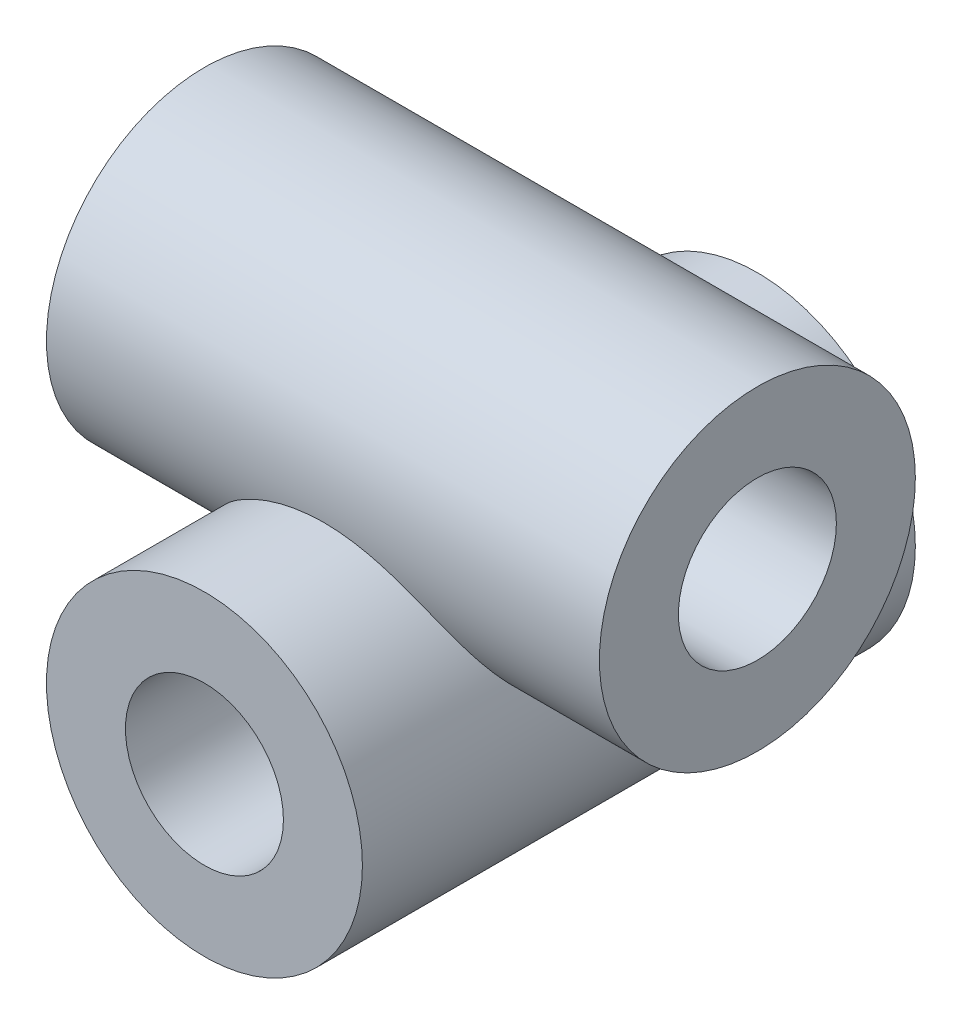
SolidWorks part; units mm, degrees
ref_plane "Front Plane" through (0, 0, 0) normal (0, 0, 1) x (1, 0, 0)
ref_plane "Top Plane" through (0, 0, 0) normal (0, 1, 0) x (1, 0, 0)
ref_plane "Right Plane" through (0, 0, 0) normal (1, 0, 0) x (0, 0, -1)
sketch "Sketch2" plane through (0, 0, 0) normal (0, 0, 1) x (1, 0, 0)
  circle A0 centre (0, 0) radius 16
  circle A1 centre (0, 0) radius 8
  dimension "D1" = 32
  dimension "D2" = 16
extrude "Boss-Extrude1" add sketch "Sketch2" along normal blind 56
sketch "Sketch3" plane through (0, 0, 0) normal (1, 0, 0) x (0, 0, -1)
  line L0 (0, 0) -> (0, 18)
  line L1 (0, 18) -> (-56, 18)
  line L2 (-56, 18) -> (-56, 0)
  line L3 (-56, 16) -> (-56, -16) construction
  circle A0 centre (-28, 18) radius 16
  circle A1 centre (-28, 18) radius 8
  dimension "D2" = 32
  dimension "D3" = 16
  dimension "D1" = 18
extrude "Boss-Extrude2" add sketch "Sketch3" along normal mid plane 56 contours A1 L1 A0 | A1 L1 A0
sketch "Sketch4" plane through (0, 0, 0) normal (1, 0, 0) x (0, 0, -1)
  circle A0 centre (-28, 18) radius 8
extrude "Cut-Extrude1" cut sketch "Sketch4" against normal mid plane 56
sketch "Sketch5" plane through (0, 0, 0) normal (0, 0, 1) x (1, 0, 0)
  circle A0 centre (0, 0) radius 8
extrude "Cut-Extrude2" cut sketch "Sketch5" along normal blind 56
